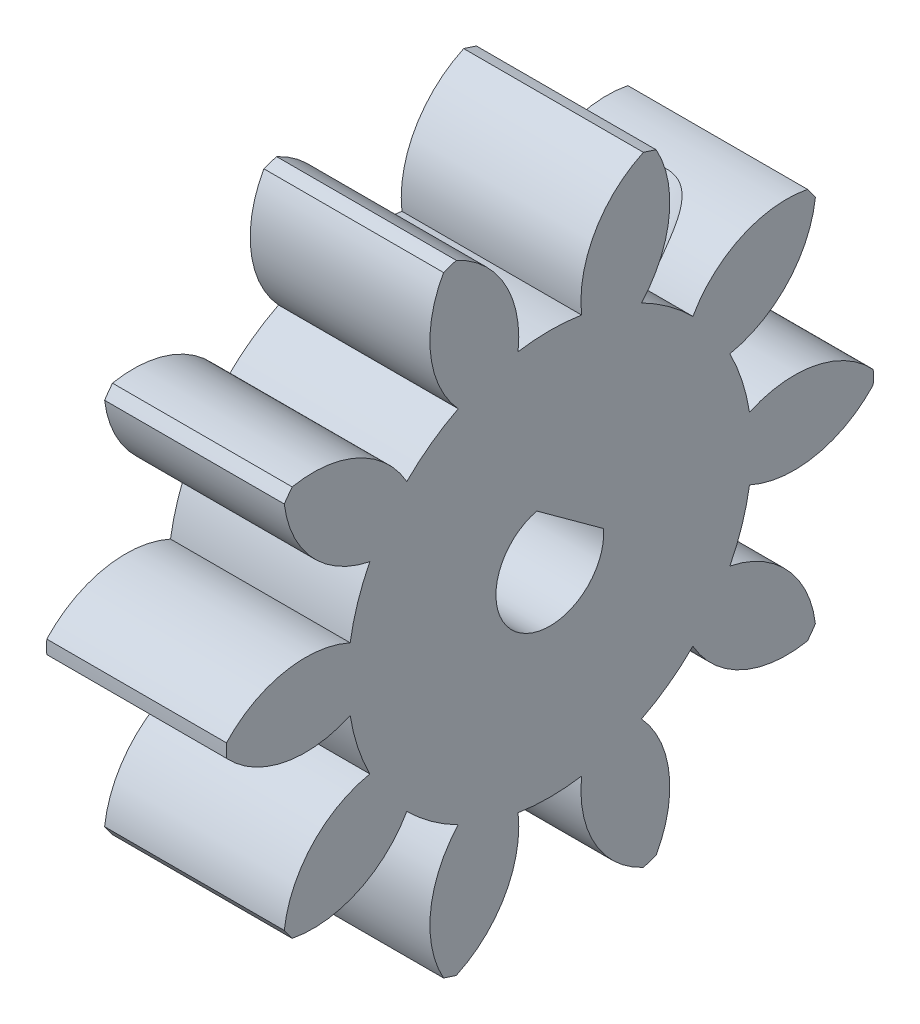
SolidWorks part; units mm, degrees
ref_plane "Plane1" through (0, 0, 0) normal (0, 0, 1) x (1, 0, 0)
ref_plane "Plane2" through (0, 0, 0) normal (0, 1, 0) x (1, 0, 0)
ref_plane "Plane3" through (0, 0, 0) normal (1, 0, 0) x (0, 0, -1)
sketch "HoldingSke" plane through (0, 0, 0) normal (0, 1, 0) x (1, 0, 0)
  line L0 (0, 0) -> (0.6565, -0.1158)
  line L1 (-15, 0) -> (100, 0) construction
  line L2 (0, 0) -> (-2.1039, 2.3779)
  line L3 (0, 0) -> (-11.863, 4.5341)
  line L4 (0, 0) -> (8.5048, 1.4996)
  line L5 (0, 0) -> (-46.8476, -17.4728)
  line L6 (0, 0) -> (-4.1448, -2.7965)
  line L7 (-2.1039, 2.3779) -> (8.6586, 51.206)
  line L8 (-76.2, 54.61) -> (-75.7, 54.61)
  line L9 (-71.009, 38.7566) -> (-53.1078, 45.2721)
  line L10 (-76.2, 71.12) -> (104.1128, 71.12)
  line L11 (0, 0) -> (-5, 0)
  line L12 (-76.2, 101.6) -> (-76.147, 101.6)
  line L13 (24.9733, 27.94) -> (52.9518, 28.4284)
  line L14 (24.9733, 27.94) -> (24.9743, 27.94)
  line L15 (24.9733, 27.94) -> (100.4006, 29.5858)
  line L16 (-63.627, -1.5) -> (-12.827, -1.5)
  circle A0 centre (0, 0) radius 1.5
  circle A1 centre (0, 0) radius 5.624
  circle A2 centre (0, 0) radius 37.5
  circle A3 centre (0, 0) radius 1.5
  dimension "MHD" = 11.248
  dimension "Hub_dia" = 75
  dimension "Bore" = 3
  dimension "MBD" = 3
  dimension "Num_teeth" = 10
  dimension "Pitch" = 0.6667
  dimension "Overall_len" = 50
  dimension "Show_teeth" = 10
  dimension "Thickness" = 5
  dimension "OAL" = 50.0002
  dimension "T_dim" = 0.5
  dimension "Ap" = 20
  dimension "H" = 19.05
  dimension "Pitch_radius" = 180.3128
  dimension "Width" = 5
  dimension "Backlash" = 0.053
  dimension "Addendum_fac" = 1
  dimension "Dedendum_fac" = 1.25
  dimension "Clearance_fac" = 0.25
  dimension "Dedendum_add" = 0.001
  dimension "Module" = 1.5
sketch "BasProSke" plane through (0, 0, 0) normal (0, 1, 0) x (1, 0, 0)
  line L0 (-10, 0) -> (60, 0) construction
  line L1 (0, 0) -> (0, 9)
  line L2 (0, 0) -> (5, 0)
  line L3 (5, 0) -> (5, 9)
  line L4 (5, 9) -> (0, 9)
  dimension "Thickness" = 5
  dimension "Diameter" = 18
revolve "Base-Revolve" add sketch "BasProSke" angle 360 about L0
sketch "TooCutSke" plane through (0, 0, 0) normal (1, 0, 0) x (0, 0, -1)
  line L1 (0, 0) -> (0, 107) construction
  line L2 (0, 0) -> (-1.2658, 7.3924) construction
  line L3 (0, 0) -> (-4.5869, 14.117) construction
  line L4 (-1.2658, 7.3924) -> (-2.2934, 7.0585) construction
  arc A0 (0.8839, 5.5541) -> (-0.8839, 5.5541) centre (0, 0) ccw
  arc A1 (2.6378, 8.6313) -> (-2.6378, 8.6313) centre (0, 0) ccw
  circle A2 centre (0, 0) radius 7.5 construction
  circle A3 centre (0, 0) radius 7.0477 construction
  arc A4 (-0.8839, 5.5541) -> (-2.6378, 8.6313) centre (-3.8646, 5.8936) ccw
  arc A5 (2.6378, 8.6313) -> (0.8839, 5.5541) centre (3.8646, 5.8936) ccw
  dimension "Root_dia" = 11.248
  dimension "Overcut_dia" = 18.0508
  dimension "Pitch_dia" = 15
  dimension "Base_dia" = 14.0954
  dimension "Flank_rad" = 3
  dimension "Half_ang" = 18
  dimension "Half_CT" = 1.0805
extrude "ToothCut" cut sketch "TooCutSke" along normal through all
fillet "Breaks" [suppressed] radius 0.03
fillet "RootFillets" [suppressed] radius 0.376
pattern_circular "TeethCuts" count 10 every 36 about axis through (-10, 0, 0) along (1, 0, 0) of "ToothCut", "RootFillets", "Breaks"
sketch "HubNeaOneSke" plane through (0, 0, 0) normal (-1, 0, 0) x (0, 0, 1)
  circle A0 centre (0, 0) radius 5.624
  dimension "Diameter" = 11.248
extrude "HubNearOne" [suppressed] add sketch "HubNeaOneSke" along normal blind 45.0002
sketch "HubNeaBotSke" plane through (0, 0, 0) normal (-1, 0, 0) x (0, 0, 1)
  circle A0 centre (0, 0) radius 5.624
  dimension "Diameter" = 11.248
extrude "HubNearBoth" [suppressed] add sketch "HubNeaBotSke" along normal blind 22.5001
ref_plane "FarPln" through (5, 0, 0) normal (1, 0, 0) x (0, 0, -1)
sketch "HubFarSke" plane through (5, 0, 0) normal (1, 0, 0) x (0, 0, -1)
  circle A0 centre (0, 0) radius 5.624
  dimension "Diameter" = 11.248
extrude "HubFar" [suppressed] add sketch "HubFarSke" along normal blind 22.5001
sketch "BorSke" plane through (0, 0, 0) normal (1, 0, 0) x (0, 0, -1)
  circle A0 centre (0, 0) radius 1.5
  dimension "Diameter" = 3
extrude "Bore" cut sketch "BorSke" along normal mid plane 100.0003
sketch "KeySke" plane through (0, 0, 0) normal (1, 0, 0) x (0, 0, -1)
  line L0 (-0.6, 0) -> (-0.6, 2)
  line L1 (-0.6, 2) -> (0.6, 2)
  line L2 (0.6, 2) -> (0.6, 0)
  line L3 (0, 0) -> (0, 34) construction
  line L4 (-0.6, 0) -> (0.6, 0)
  dimension "Offset" = 2
  dimension "Width" = 1.2
extrude "Keyway" [suppressed] cut sketch "KeySke" along normal mid plane 100.0003
pattern_circular "Keyway2" [suppressed] count 2 every 90 about axis through (-10, 0, 0) along (1, 0, 0)
sketch "草圖2" plane through (0, 0, 0) normal (1, 0, 0) x (0, 0, -1)
  line L0 (-0.3643, 1.4551) -> (1.4964, 0.1032)
  line L1 (3.9797, 3.9738) -> (1.4964, 0.1032) construction
  line L2 (2.5496, 5.0129) -> (-0.3643, 1.4551) construction
  arc A1 (-0.3643, 1.4551) -> (1.4964, 0.1032) centre (0, 0) cw
  dimension "D1" = 1.5
  dimension "D2" = 2.3
extrude "填料-伸長1" add sketch "草圖2" along normal through all contours A1 L0
sketch "草圖3" plane through (0, 0.7791, -0.5661) normal (0, -0.809, 0.5878) x (1, 0, 0)
  line L0 (0, 1.15) -> (5, -1.15) construction
  line L1 (5, 1.15) -> (0, -1.15) construction
  circle A0 centre (2.5, 0) radius 1.5
  dimension "D1" = 3
extrude "除料-伸長1" cut sketch "草圖3" against normal blind 7
equation "' \"Module@HoldingSke\" = 6.35"
equation "' \"Num_teeth@HoldingSke\" = 12"
equation "' \"Width@HoldingSke\" = 0.5 * 25.4"
equation "' \"Hub_dia@HoldingSke\"= 1 * 25.4"
equation "' \"Hub_dia@HoldingSke\" = 1 * 25.4"
equation "' \"Overall_len@HoldingSke\" = 1.0 * 25.4"
equation "' \"Bore@HoldingSke\" = 0.75 * 25.4"
equation "' \"T_dim@HoldingSke\" = 0.1 * 25.4"
equation "' \"Width@KeySke\" = 0.25 * 25.4"
equation "' \"Show_teeth@HoldingSke\" = 13"
equation "' \"Backlash@HoldingSke\" = 0.009 * 25.4"
equation "' \"Addendum_fac@HoldingSke\" = 1.0"
equation "' \"Dedendum_fac@HoldingSke\" = 1.25"
equation "' \"Dedendum_add@HoldingSke\" = 0.00005 * 25.4"
equation "' \"Clearance_fac@HoldingSke\" = 0.25"
equation "\"Pitch@HoldingSke\" = 1 / \"Module@HoldingSke\""
equation "\"Overcut_dia@TooCutSke\" = (\"Num_teeth@HoldingSke\" + 2 * \"Addendum_fac@HoldingSke\") / \"Pitch@HoldingSke\" + 0.002 * 25.4"
equation "\"Pitch_dia@TooCutSke\" = \"Num_teeth@HoldingSke\" / \"Pitch@HoldingSke\""
equation "\"Base_dia@TooCutSke\" = \"Num_teeth@HoldingSke\" / \"Pitch@HoldingSke\" * cos((\"Ap@HoldingSke\"  * 3.14159265 / 180))"
equation "\"Root_dia@TooCutSke\" = (\"Num_teeth@HoldingSke\" + 2) / \"Pitch@HoldingSke\" - 2 * (\"Addendum_fac@HoldingSke\" + \"Dedendum_fac@HoldingSke\") / \"Pitch@HoldingSke\" - \"Dedendum_add@HoldingSke\" * 2"
equation "\"Half_ang@TooCutSke\" = 180 / \"Num_teeth@HoldingSke\""
equation "\"Half_CT@TooCutSke\" = \"Num_teeth@HoldingSke\" / \"Pitch@HoldingSke\" * sin((3.14159265 / 2 / \"Num_teeth@HoldingSke\")) / 2 - 7 * \"Backlash@HoldingSke\" / 4"
equation "\"Flank_rad@TooCutSke\" = \"Num_teeth@HoldingSke\" / \"Pitch@HoldingSke\" / 5"
equation "\"Radius@RootFillets\" = \"Clearance_fac@HoldingSke\" / \"Pitch@HoldingSke\" + \"Dedendum_add@HoldingSke\""
equation "\"Break_rad@Breaks\" = 0.02 / \"Pitch@HoldingSke\""
equation "\"Thickness@HoldingSke\" = \"Width@HoldingSke\""
equation "\"OAL@HoldingSke\" = \"Thickness@HoldingSke\""
equation "\"MHD@HoldingSke\" = (\"Num_teeth@HoldingSke\" + 2) / \"Pitch@HoldingSke\" - 2 * (\"Addendum_fac@HoldingSke\" + \"Dedendum_fac@HoldingSke\")  / \"Pitch@HoldingSke\" - \"Dedendum_add@HoldingSke\" * 2"
equation "\"MBD@HoldingSke\" = (\"Num_teeth@HoldingSke\" + 2) / \"Pitch@HoldingSke\" - 2 * (\"Addendum_fac@HoldingSke\" + \"Dedendum_fac@HoldingSke\")  / \"Pitch@HoldingSke\" - \"Dedendum_add@HoldingSke\" * 2 - 0.002 * 25.4"
equation "\"MHD@HoldingSke\" = ((sgn( \"MHD@HoldingSke\" - \"Hub_dia@HoldingSke\" )-1)*( \"MHD@HoldingSke\" - \"Hub_dia@HoldingSke\" ))/-2+ \"Hub_dia@HoldingSke\""
equation "\"MBD@HoldingSke\" = ((sgn( \"MBD@HoldingSke\" - \"Bore@HoldingSke\" )-1)*( \"MBD@HoldingSke\" - \"Bore@HoldingSke\" ))/-2+ \"Bore@HoldingSke\""
equation "\"OAL@HoldingSke\" = ((sgn( \"OAL@HoldingSke\" - \"Overall_len@HoldingSke\" )+1)*( \"OAL@HoldingSke\" - \"Overall_len@HoldingSke\" ))/2 + \"Overall_len@HoldingSke\" + 0.000002 * 25.4"
equation "\"Num_teeth@TeethCuts\" = int( \"Show_teeth@HoldingSke\" ) + 1"
equation "\"Num_teeth@TeethCuts\" = ((sgn( \"Num_teeth@TeethCuts\" - \"Num_teeth@HoldingSke\" )-1)*( \"Num_teeth@TeethCuts\" - \"Num_teeth@HoldingSke\" ))/-2+ \"Num_teeth@HoldingSke\""
equation "\"Num_teeth@TeethCuts\" = ((sgn( \"Num_teeth@TeethCuts\" - 2.0)+1)*( \"Num_teeth@TeethCuts\" - 2.0))/2 +2.0"
equation "\"Angle@TeethCuts\" = 360.0 / \"Num_teeth@HoldingSke\""
equation "\"Diameter@BasProSke\" = (\"Num_teeth@HoldingSke\" + 2 * \"Addendum_fac@HoldingSke\") / \"Pitch@HoldingSke\""
equation "\"Thickness@BasProSke\"  = \"Thickness@HoldingSke\""
equation "' \"Fillet_rad@BasProSke\" =  \"Thickness@HoldingSke\" * 0.05"
equation "' \"Fillet_rad@BasProSke\" = \"Thickness@HoldingSke\" * 0.05"
equation "\"MHD@HoldingSke\" = ((sgn( \"MHD@HoldingSke\" - \"Root_dia@TooCutSke\" )-1)*( \"MHD@HoldingSke\" - \"Root_dia@TooCutSke\" ))/-2+ \"Root_dia@TooCutSke\""
equation "\"Diameter@HubNeaOneSke\" = \"MHD@HoldingSke\""
equation "\"Length@HubNearOne\" = \"OAL@HoldingSke\" - \"Thickness@BasProSke\""
equation "\"Diameter@HubNeaBotSke\" = \"MHD@HoldingSke\""
equation "\"Length@HubNearBoth\" = ( \"OAL@HoldingSke\" - \"Thickness@BasProSke\" ) / 2.0"
equation "\"Thickness@FarPln\" = \"Thickness@BasProSke\""
equation "\"Diameter@HubFarSke\" = \"MHD@HoldingSke\""
equation "\"Length@HubFar\" = ( \"OAL@HoldingSke\" - \"Thickness@BasProSke\" ) / 2.0"
equation "\"Diameter@BorSke\" = \"MBD@HoldingSke\""
equation "\"D1@Bore\" = \"OAL@HoldingSke\" * 2.0"
equation "\"D1@Keyway\" = \"OAL@HoldingSke\" * 2.0"
equation "\"Offset@KeySke\" = \"T_dim@HoldingSke\" + \"MBD@HoldingSke\" / 2.0"
